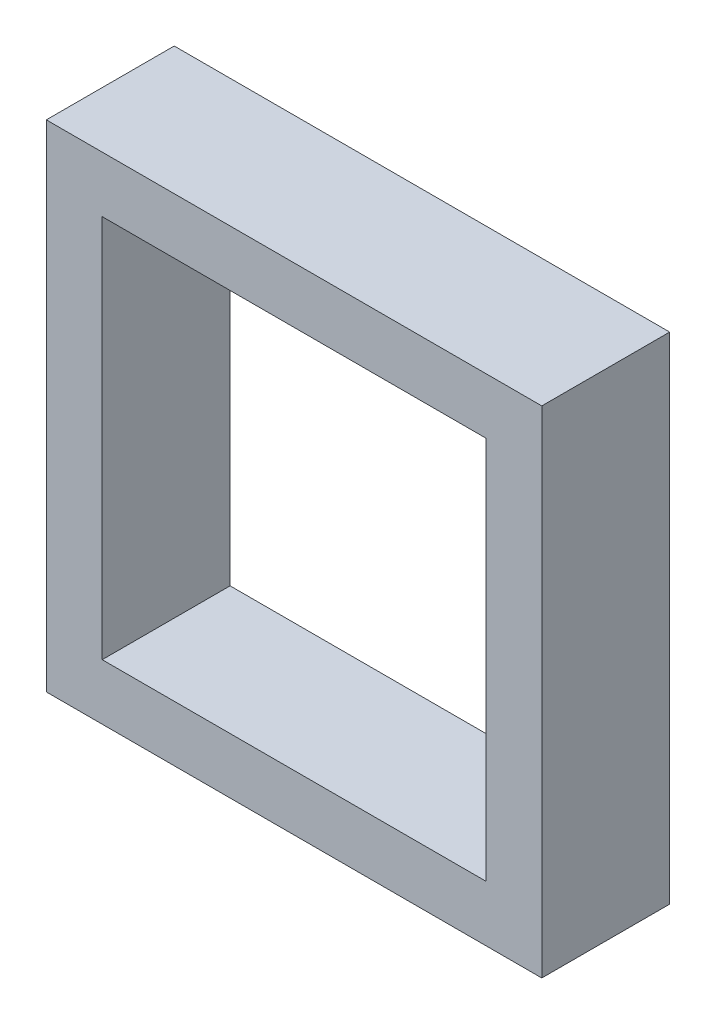
SolidWorks part; units mm, degrees
ref_plane "Front Plane" through (0, 0, 0) normal (0, 0, 1) x (1, 0, 0)
ref_plane "Top Plane" through (0, 0, 0) normal (0, 1, 0) x (1, 0, 0)
ref_plane "Right Plane" through (0, 0, 0) normal (1, 0, 0) x (0, 0, -1)
sketch "Sketch1" plane through (0, 0, 0) normal (0, 0, 1) x (1, 0, 0)
  line L1 (-15, 15) -> (15, 15)
  line L2 (-15, 15) -> (-15, -15)
  line L3 (-15, -15) -> (15, -15)
  line L4 (15, 15) -> (15, -15)
  line L5 (-15, 15) -> (15, -15) construction
  line L6 (-15, -15) -> (15, 15) construction
  line L7 (19.3689, 19.3689) -> (-19.3689, 19.3689)
  line L8 (19.3689, 19.3689) -> (19.3689, -19.3689)
  line L9 (19.3689, -19.3689) -> (-19.3689, -19.3689)
  line L10 (-19.3689, 19.3689) -> (-19.3689, -19.3689)
  line L11 (19.3689, 19.3689) -> (-19.3689, -19.3689) construction
  line L12 (19.3689, -19.3689) -> (-19.3689, 19.3689) construction
  point P0 (0, 0)
  point P6 (0, 0)
  point P11 (-92.5056, -29.398)
extrude "Boss-Extrude1" add sketch "Sketch1" along normal blind 10
